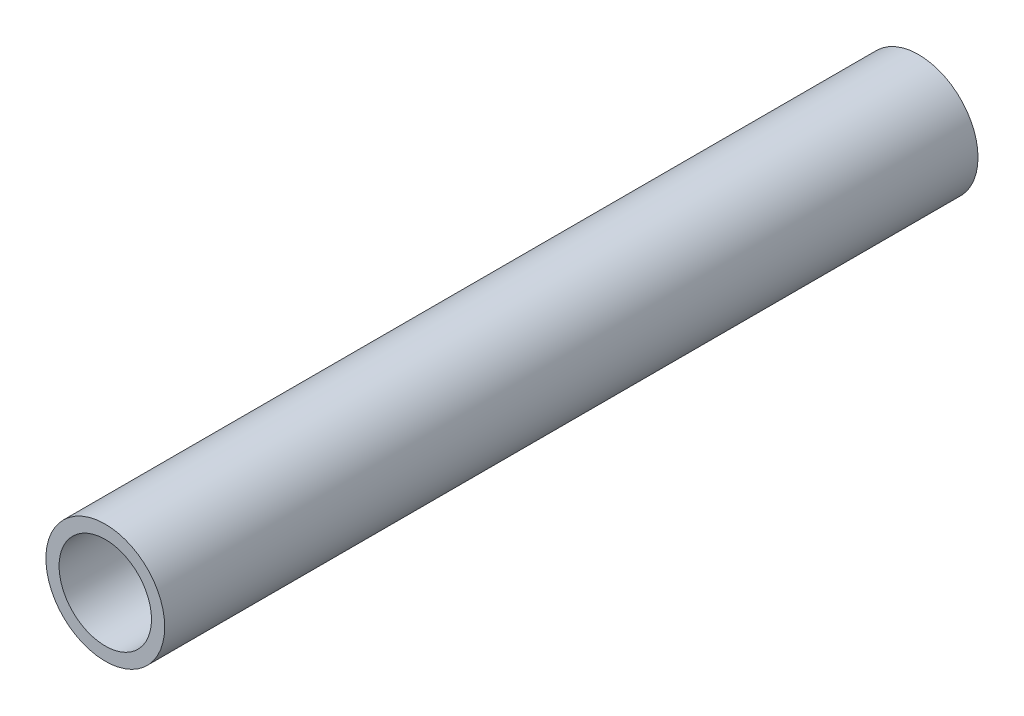
SolidWorks part; units mm, degrees
ref_plane "Front Plane" through (0, 0, 0) normal (0, 0, 1) x (1, 0, 0)
ref_plane "Top Plane" through (0, 0, 0) normal (0, 1, 0) x (1, 0, 0)
ref_plane "Right Plane" through (0, 0, 0) normal (1, 0, 0) x (0, 0, -1)
sketch "Sketch1" plane through (0, 0, 0) normal (0, 0, 1) x (1, 0, 0)
  circle A0 centre (0, 0) radius 9
  circle A1 centre (0, 0) radius 7
  dimension "D1" = 14
  dimension "D2" = 18
extrude "Boss-Extrude1" add sketch "Sketch1" along normal mid plane 123.22
